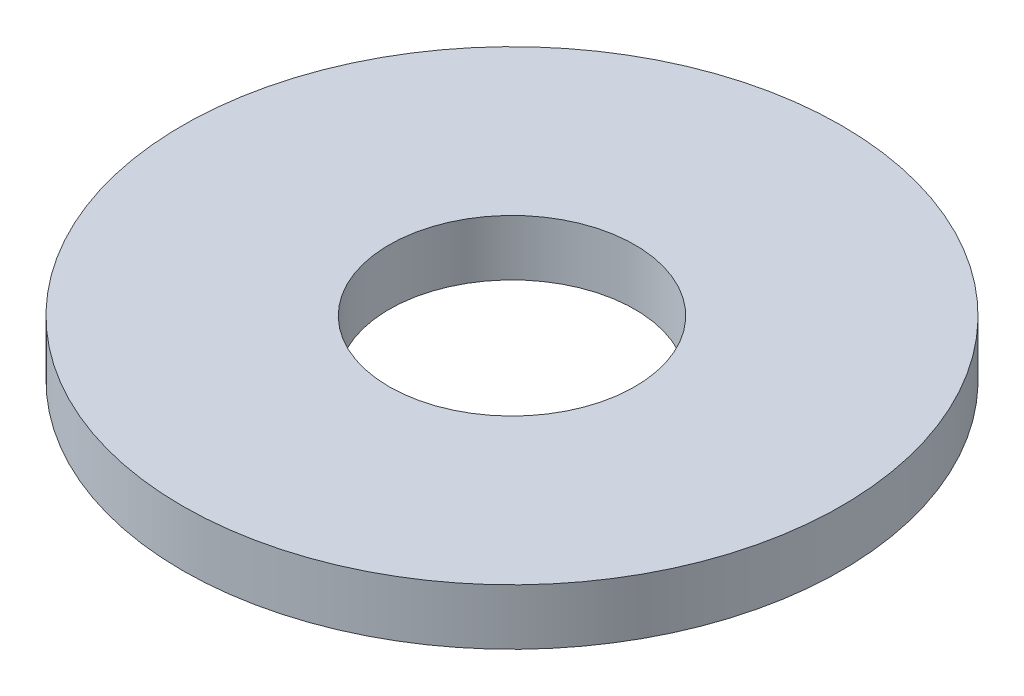
SolidWorks part; units mm, degrees
material "Plain Carbon Steel"
ref_plane "Front Plane" through (0, 0, 0) normal (0, 0, 1) x (1, 0, 0)
ref_plane "Top Plane" through (0, 0, 0) normal (0, 1, 0) x (1, 0, 0)
ref_plane "Right Plane" through (0, 0, 0) normal (1, 0, 0) x (0, 0, -1)
sketch "Sketch1" plane through (0, 0, 0) normal (0, 1, 0) x (1, 0, 0)
  circle A0 centre (0, 0) radius 5.9
  circle A1 centre (0, 0) radius 2.2
  dimension "D1" = 11.8
  dimension "D2" = 4.4
extrude "Boss-Extrude1" add sketch "Sketch1" along normal blind 1
